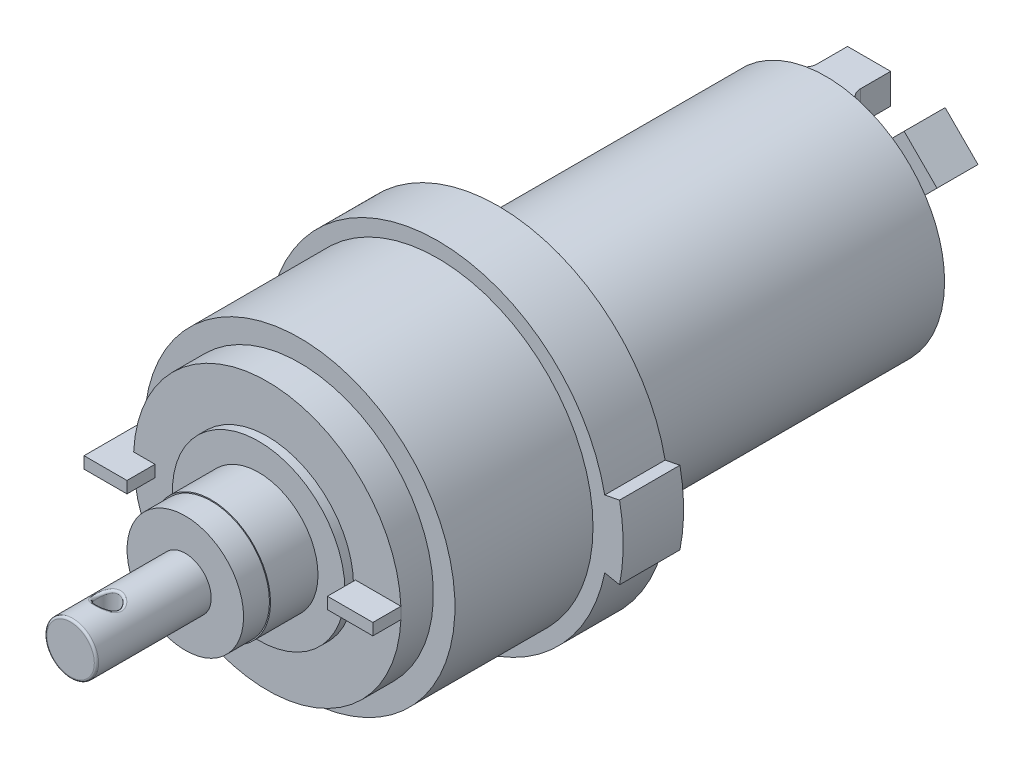
SolidWorks part; units mm, degrees
ref_plane "Front Plane" through (0, 0, 0) normal (0, 0, 1) x (1, 0, 0)
ref_plane "Top Plane" through (0, 0, 0) normal (0, 1, 0) x (1, 0, 0)
ref_plane "Right Plane" through (0, 0, 0) normal (1, 0, 0) x (0, 0, -1)
sketch "Sketch1" plane through (0, 0, 0) normal (0, 0, 1) x (1, 0, 0)
  circle A0 centre (0, 0) radius 13.75
  dimension "D1" = 27.5
extrude "MotorBody" add sketch "Sketch1" against normal blind 38
sketch "Sketch2" plane through (0, 0, 0) normal (0, 0, 1) x (1, 0, 0)
  line L0 (0, 24.005) -> (0, -23.4732) construction
  line L1 (-25.2916, 0) -> (24.858, 0) construction
  line L2 (21.5, 0) -> (21.5, 4.25) construction
  line L3 (21.5, 0) -> (21.5, -4.25) construction
  line L4 (19.3603, 3.9041) -> (21.0758, 4.25)
  line L5 (19.3603, -3.9041) -> (21.0758, -4.25)
  line L6 (-19.3603, -3.9041) -> (-21.0758, -4.25)
  line L7 (-19.3603, 3.9041) -> (-21.0758, 4.25)
  arc A0 (-19.3603, -3.9041) -> (19.3603, -3.9041) centre (0, 0) ccw
  arc A1 (-21.0758, 4.25) -> (-21.0758, -4.25) centre (0, 0) ccw
  arc A2 (21.0758, -4.25) -> (21.0758, 4.25) centre (0, 0) ccw
  arc A3 (19.3603, 3.9041) -> (-19.3603, 3.9041) centre (0, 0) ccw
  dimension "D1" = 39.5
  dimension "D2" = 43
  dimension "D3" = 4.25
  dimension "D4" = 4.25
extrude "Plastic Cap" add sketch "Sketch2" along normal blind 7
sketch "Sketch3" plane through (0, 0, 7) normal (0, 0, 1) x (1, 0, 0)
  circle A0 centre (0, 0) radius 18
  dimension "D1" = 36
extrude "Boss-Extrude3" add sketch "Sketch3" along normal blind 16
sketch "Sketch4" plane through (0, 0, 23) normal (0, 0, 1) x (1, 0, 0)
  circle A0 centre (0, 0) radius 15.5
  dimension "D1" = 31
extrude "Boss-Extrude4" add sketch "Sketch4" along normal blind 3.75
sketch "Sketch5" plane through (0, 0, 26.75) normal (0, 0, 1) x (1, 0, 0)
  circle A0 centre (0, 0) radius 10
  dimension "D1" = 20
extrude "Boss-Extrude5" add sketch "Sketch5" along normal blind 1
sketch "Sketch6" plane through (0, 0, 27.75) normal (0, 0, 1) x (1, 0, 0)
  circle A0 centre (0, 0) radius 6.875
  dimension "D1" = 13.75
extrude "Boss-Extrude6" add sketch "Sketch6" along normal blind 5.5
sketch "Sketch7" plane through (0, 0, 33.25) normal (0, 0, 1) x (1, 0, 0)
  circle A0 centre (0, 0) radius 6.75
  dimension "D1" = 13.5
extrude "Washers" add sketch "Sketch7" along normal blind 3
sketch "Sketch8" plane through (0, 0, 36.25) normal (0, 0, 1) x (1, 0, 0)
  circle A0 centre (0, 0) radius 3
  dimension "D1" = 6
extrude "Shaft" add sketch "Sketch8" along normal blind 13.3
sketch "Sketch9" plane through (0, 0, 23) normal (0, 0, 1) x (1, 0, 0)
  line L0 (-25.6389, 0) -> (24.8596, 0) construction
  line L2 (-13.0127, 0.6758) -> (-17.9873, 0.6758)
  line L3 (-13.0127, 0.6758) -> (-13.0127, -0.6758)
  line L4 (-13.0127, -0.6758) -> (-17.9873, -0.6758)
  line L5 (-17.9873, 0.6758) -> (-17.9873, -0.6758)
  line L6 (-13.0127, 0.6758) -> (-17.9873, -0.6758) construction
  line L7 (-13.0127, -0.6758) -> (-17.9873, 0.6758) construction
  line L8 (10.2236, 0.6758) -> (15.4853, 0.6758)
  line L9 (10.2236, 0.6758) -> (10.2236, -0.6758)
  line L10 (10.2236, -0.6758) -> (15.4853, -0.6758)
  line L11 (15.4853, 0.6758) -> (15.4853, -0.6758)
  line L12 (10.2236, 0.6758) -> (15.4853, -0.6758) construction
  line L13 (10.2236, -0.6758) -> (15.4853, 0.6758) construction
  circle A0 centre (0, 0) radius 12.8544 construction
  circle A1 centre (0, 0) radius 15.5 construction
  circle A2 centre (0, 0) radius 18 construction
  point P5 (-15.5, 0)
  point P14 (12.8544, 0)
extrude "squaresStickingOut" add sketch "Sketch9" along normal blind 7
sketch "Sketch10" plane through (0, 0, 0) normal (0, 1, 0) x (1, 0, 0)
  line L0 (8.021, -36.25) -> (8.021, -45.25) construction
  circle A0 centre (0, -45.25) radius 1.25
  dimension "D2" = 2.5
  dimension "D1" = 9
extrude "HoleInShaft" cut sketch "Sketch10" against normal mid plane 7
fillet "Fillet4" radius 0.25 1 edges at (3, 0, 49.55)
sketch "Sketch11" plane through (0, 0, -38) normal (0, 0, -1) x (-1, 0, 0)
  line L0 (0, 21.0184) -> (0, -21.5292) construction
  line L1 (-27.1732, 0) -> (25.8963, 0) construction
  line L2 (-2.5, 12.9992) -> (2.5, 12.9992)
  line L3 (-2.5, 12.9992) -> (-2.5, 9.4992)
  line L4 (-2.5, 9.4992) -> (2.5, 9.4992)
  line L5 (2.5, 12.9992) -> (2.5, 9.4992)
  line L6 (-2.5, 12.9992) -> (2.5, 9.4992) construction
  line L7 (-2.5, 9.4992) -> (2.5, 12.9992) construction
  line L8 (-2.5, -12.9992) -> (-2.5, -9.4992)
  line L9 (-2.5, -12.9992) -> (2.5, -12.9992)
  line L10 (2.5, -12.9992) -> (2.5, -9.4992)
  line L11 (-2.5, -9.4992) -> (2.5, -9.4992)
  point P3 (0, 11.2492)
  point P14 (0, -11.2492)
  dimension "D1" = 3.5
  dimension "D2" = 5
extrude "Boss-Extrude10" add sketch "Sketch11" along normal blind 5
sketch "Sketch12" plane through (0, 0, -38) normal (0, 0, -1) x (-1, 0, 0)
  line L0 (0, 0) -> (-15.668, 15.668) construction
  line L1 (-12.8715, 8.9543) -> (-7.0025, 3.0853)
  line L2 (-7.0025, 3.0853) -> (-3.1923, 6.8955)
  line L3 (-3.1923, 6.8955) -> (-9.0614, 12.7645)
  line L4 (-9.0614, 12.7645) -> (-12.8715, 8.9543)
  circle A0 centre (0, 0) radius 8.9543 construction
extrude "Boss-Extrude11" add sketch "Sketch12" along normal blind 4.75
fillet "Fillet5" radius 1.5 6 edges at (2.5, 11.2492, -38) (-2.5, 11.2492, -38) (0, 9.4992, -38) (2.5, -11.2492, -38) (0, -9.4992, -38) (-2.5, -11.2492, -38)
fillet "Fillet6" radius 0.25 2 edges at (-0.1727, -2.995, 44.012) (0.1727, 2.995, 44.012)
